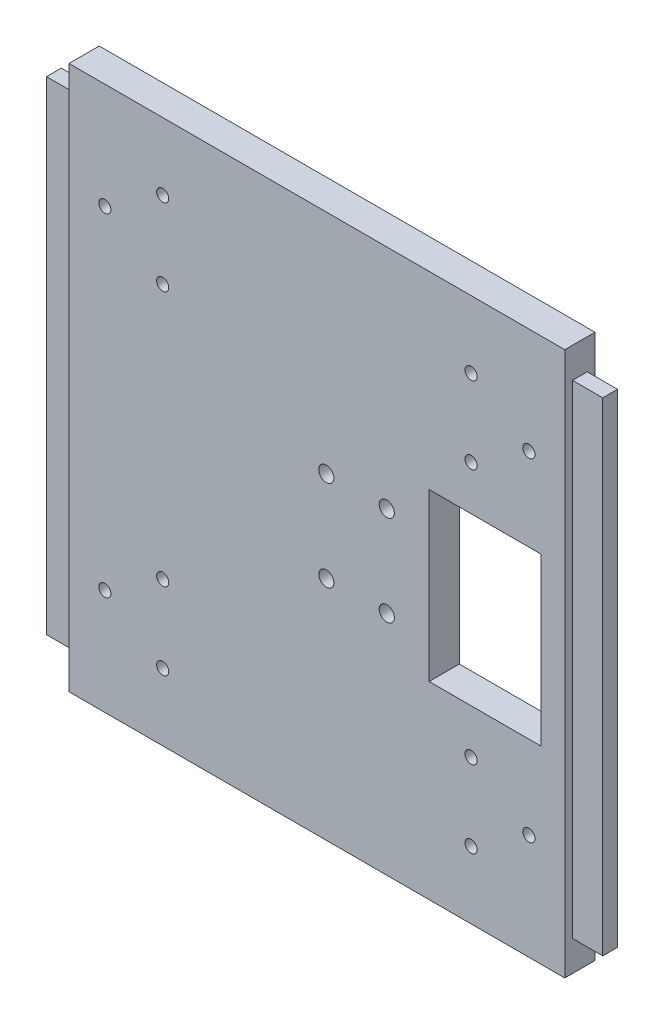
SolidWorks part; units mm, degrees
ref_plane "前视基准面" through (0, 0, 0) normal (0, 0, 1) x (1, 0, 0)
ref_plane "上视基准面" through (0, 0, 0) normal (0, 1, 0) x (1, 0, 0)
ref_plane "右视基准面" through (0, 0, 0) normal (1, 0, 0) x (0, 0, -1)
other "Configuration Table"
sketch "草图1" plane through (0, 0, 0) normal (0, 0, 1) x (1, 0, 0)
  line L1 (0, 0) -> (164, 0)
  line L2 (0, 0) -> (0, 180)
  line L3 (0, 180) -> (164, 180)
  line L4 (164, 0) -> (164, 180)
  line L5 (0, 0) -> (164, 180) construction
  line L6 (0, 180) -> (164, 0) construction
  point P4 (82, 90)
  dimension "D1" = 164
  dimension "D2" = 180
extrude "凸台-拉伸1" add sketch "草图1" along normal blind 10
sketch "草图2" plane through (0, 0, 0) normal (-1, 0, 0) x (0, 0, 1)
  line L0 (10, 180) -> (10, 0) construction
  line L1 (2.56, 169.94) -> (7.44, 169.94)
  line L2 (2.56, 169.94) -> (2.56, 10.06)
  line L3 (2.56, 10.06) -> (7.44, 10.06)
  line L4 (7.44, 169.94) -> (7.44, 10.06)
  line L5 (2.56, 169.94) -> (7.44, 10.06) construction
  line L6 (2.56, 10.06) -> (7.44, 169.94) construction
  line L7 (10, 180) -> (0, 180) construction
  point P4 (5, 90)
  dimension "D1" = 4.88
  dimension "D2" = 159.88
  dimension "D3" = 5
  dimension "D4" = 90
extrude "凸台-拉伸2" add sketch "草图2" along normal blind 10
ref_plane "基准面1" through (82, 0, 0) normal (1, 0, 0) x (0, 0, -1)
mirror "镜向1" about plane through (82, 0, 0) normal (1, 0, 0) of "凸台-拉伸2"
sketch "草图3" plane through (0, 0, 0) normal (0, 0, -1) x (-1, 0, 0)
  line L0 (-164, 169.94) -> (-164, 10.06) construction
  line L1 (-164, 90) -> (12.5762, 90) construction
  line L2 (-174, 169.94) -> (-174, 10.06) construction
  line L3 (-164, 0) -> (-164, 180) construction
  line L4 (0, 169.94) -> (0, 10.06) construction
  line L5 (0, 180) -> (0, 0) construction
  circle A0 centre (-152.1426, 145) radius 2
  circle A1 centre (-133, 157.75) radius 2
  circle A2 centre (-133, 132.25) radius 2
  circle A3 centre (-11.8574, 145) radius 2
  circle A4 centre (-31, 157.75) radius 2
  circle A5 centre (-31, 132.25) radius 2
  circle A6 centre (-133, 47.75) radius 2
  circle A7 centre (-133, 22.25) radius 2
  circle A8 centre (-152.1426, 35) radius 2
  circle A9 centre (-31, 47.75) radius 2
  circle A10 centre (-31, 22.25) radius 2
  circle A11 centre (-11.8574, 35) radius 2
  dimension "D1" = 4
  dimension "D2" = 4
  dimension "D3" = 4
  dimension "D4" = 4
  dimension "D5" = 4
  dimension "D6" = 4
  dimension "D7" = 23
  dimension "D8" = 23
  dimension "D9" = 25.5
  dimension "D10" = 10
  dimension "D11" = 55
  dimension "D12" = 31
  dimension "D13" = 25.5
  dimension "D14" = 23
  dimension "D15" = 23
  dimension "D16" = 31
  dimension "D17" = 31
  dimension "D18" = 55
  dimension "D19" = 31
extrude "切除-拉伸1" cut sketch "草图3" against normal blind 10
sketch "草图5" plane through (0, 0, 10) normal (0, 0, 1) x (1, 0, 0)
  line L0 (0, 90) -> (164, 90) construction
  line L1 (85.1179, 105) -> (85.1179, 75) construction
  line L3 (0, 10.06) -> (0, 169.94) construction
  line L4 (5, 110.5) -> (125, 110.5) construction
  line L5 (5, 110.5) -> (5, 69.5) construction
  line L6 (5, 69.5) -> (125, 69.5) construction
  line L7 (125, 110.5) -> (125, 69.5) construction
  line L8 (5, 110.5) -> (125, 69.5) construction
  line L9 (5, 69.5) -> (125, 110.5) construction
  line L10 (119.1179, 117.5) -> (156.1179, 117.5)
  line L11 (75.1179, 110) -> (118.1179, 110) construction
  line L12 (75.1179, 110) -> (75.1179, 70) construction
  line L13 (75.1179, 70) -> (118.1179, 70) construction
  line L14 (118.1179, 110) -> (118.1179, 70) construction
  line L15 (75.1179, 110) -> (118.1179, 70) construction
  line L16 (75.1179, 70) -> (118.1179, 110) construction
  line L17 (119.1179, 117.5) -> (119.1179, 62.5)
  line L18 (119.1179, 62.5) -> (156.1179, 62.5)
  line L19 (156.1179, 117.5) -> (156.1179, 62.5)
  line L20 (119.1179, 117.5) -> (156.1179, 62.5) construction
  line L21 (119.1179, 62.5) -> (156.1179, 117.5) construction
  circle A1 centre (85.1179, 105) radius 2.5
  circle A2 centre (85.1179, 75) radius 2.5
  circle A5 centre (105.1179, 105) radius 2.5
  circle A6 centre (105.1179, 75) radius 2.5
  point P5 (65, 90)
  point P13 (96.6179, 90)
  point P22 (85.1179, 90)
  point P27 (137.6179, 90)
  dimension "D5" = 43
  dimension "D7" = 5
  dimension "D8" = 2
  dimension "D9" = 5
  dimension "D10" = 55
  dimension "D1" = 120
  dimension "D2" = 41
  dimension "D3" = 5
  dimension "D4" = 6.8821
  dimension "D6" = 40
  dimension "D11" = 30
  dimension "D12" = 10
  dimension "D13" = 37
  dimension "D14" = 2
extrude "切除-拉伸3" cut sketch "草图5" against normal blind 8
sketch "草图6" plane through (0, 0, 2) normal (0, 0, 1) x (1, 0, 0)
  line L4 (119.1179, 117.5) -> (119.1179, 62.5)
  line L5 (119.1179, 62.5) -> (156.1179, 62.5)
  line L6 (156.1179, 62.5) -> (156.1179, 117.5)
  line L7 (156.1179, 117.5) -> (119.1179, 117.5)
  line L8 (119.1179, 117.5) -> (119.1179, 62.5)
  line L9 (119.1179, 62.5) -> (156.1179, 62.5)
  line L10 (156.1179, 62.5) -> (156.1179, 117.5)
  line L11 (156.1179, 117.5) -> (119.1179, 117.5)
  dimension "D1" = 0
extrude "切除-拉伸4" cut sketch "草图6" against normal blind 8
